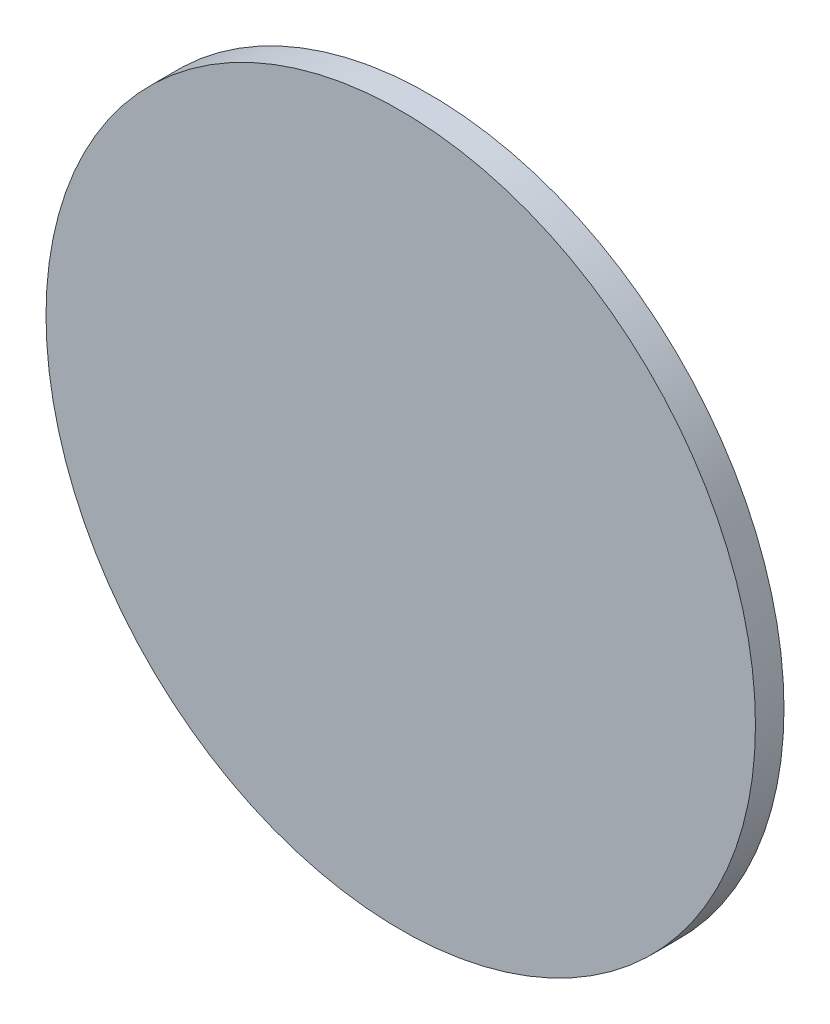
SolidWorks part; units mm, degrees
ref_plane "Front Plane" through (0, 0, 0) normal (0, 0, 1) x (1, 0, 0)
ref_plane "Top Plane" through (0, 0, 0) normal (0, 1, 0) x (1, 0, 0)
ref_plane "Right Plane" through (0, 0, 0) normal (1, 0, 0) x (0, 0, -1)
sketch "Sketch2" plane through (0, 0, 0) normal (0, 0, 1) x (1, 0, 0)
  circle A0 centre (0, 0) radius 24.875
  dimension "D1" = 49.75
extrude "Boss-Extrude1" add sketch "Sketch2" along normal blind 2
sketch "Sketch3" plane through (0, 0, 2) normal (0, 0, 1) x (1, 0, 0)
  circle A0 centre (0, 15) radius 2
  dimension "D1" = 4
  dimension "D2" = 15
